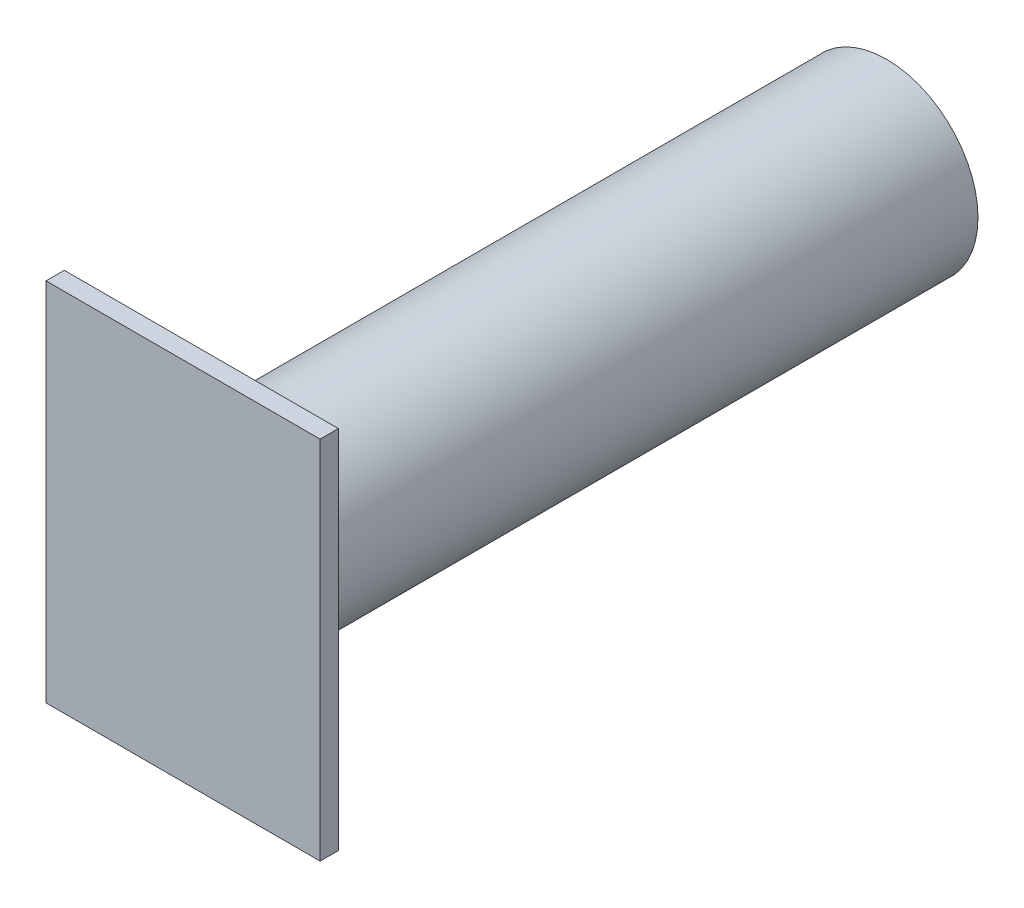
SolidWorks part; units mm, degrees
ref_plane "Alzado" through (0, 0, 0) normal (0, 0, 1) x (1, 0, 0)
ref_plane "Planta" through (0, 0, 0) normal (0, 1, 0) x (1, 0, 0)
ref_plane "Vista lateral" through (0, 0, 0) normal (1, 0, 0) x (0, 0, -1)
sketch "Croquis1" plane through (0, 0, 0) normal (0, 0, 1) x (1, 0, 0)
  circle A0 centre (0, 0) radius 10
  dimension "D1" = 20
extrude "Saliente-Extruir1" add sketch "Croquis1" along normal blind 75
sketch "Croquis2" plane through (0, 0, 75) normal (0, 0, 1) x (1, 0, 0)
  line L1 (-15, -20) -> (15, -20)
  line L2 (-15, -20) -> (-15, 20)
  line L3 (-15, 20) -> (15, 20)
  line L4 (15, -20) -> (15, 20)
  line L5 (-15, -20) -> (15, 20) construction
  line L6 (-15, 20) -> (15, -20) construction
  point P0 (0, 0)
  dimension "D1" = 30
  dimension "D2" = 40
extrude "Saliente-Extruir2" add sketch "Croquis2" along normal blind 2
